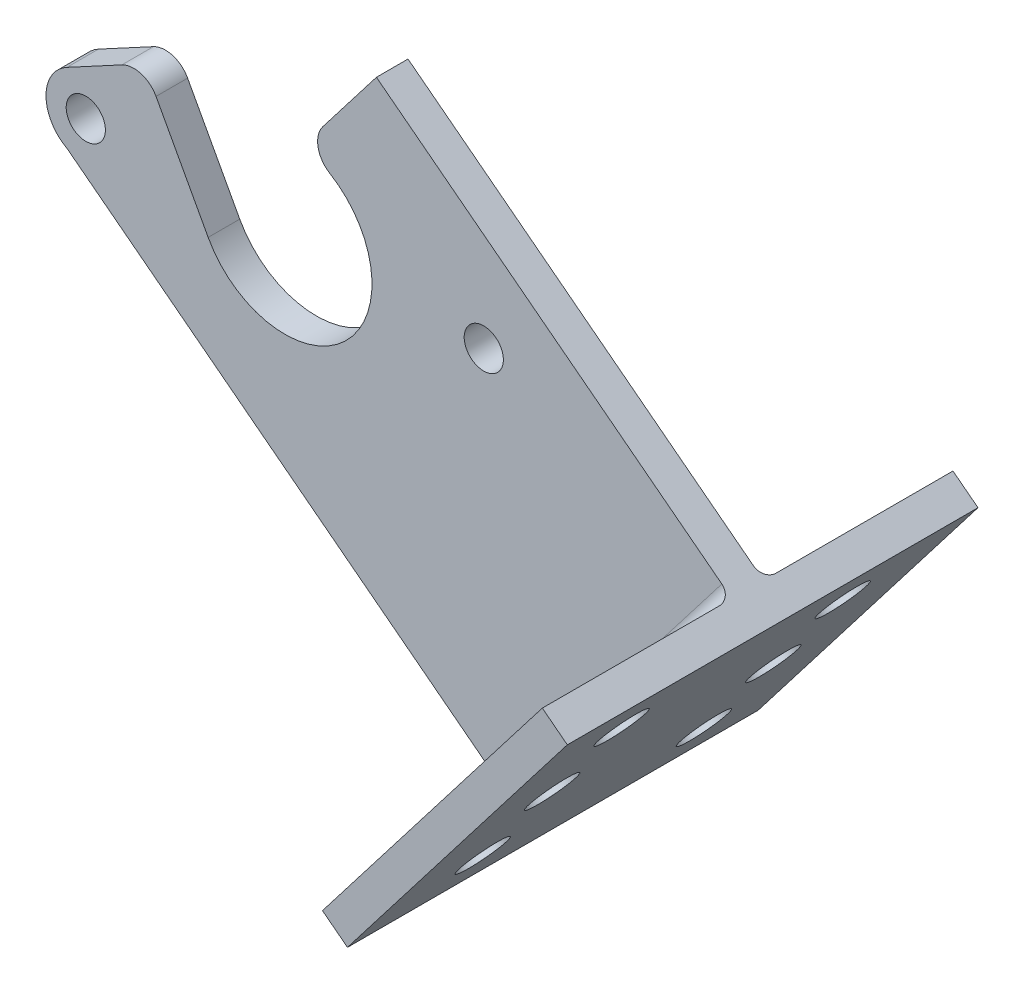
SolidWorks part; units mm, degrees
material "Galvanized Steel"
ref_plane "Front Plane" through (0, 0, 0) normal (0, 0, 1) x (1, 0, 0)
ref_plane "Top Plane" through (0, 0, 0) normal (0, 1, 0) x (1, 0, 0)
ref_plane "Right Plane" through (0, 0, 0) normal (1, 0, 0) x (0, 0, -1)
sketch "Sketch1" plane through (0, 0, 0) normal (0, 0, 1) x (1, 0, 0)
  line L0 (-66.7187, 0.4983) -> (-21.3653, 0.4983) construction
  line L1 (-41.4241, 0.4983) -> (-38.3055, -1.9046)
  line L4 (-29.7212, 15.8934) -> (-45.2196, 7.5407)
  line L6 (38.5759, 0.4983) -> (41.6945, -1.9046)
  line L7 (54.0969, -73.0994) -> (83.8977, -34.4216)
  line L8 (83.8977, -34.4216) -> (54.0969, -73.0994)
  line L9 (-45.2196, -6.544) -> (49.2783, -79.3534)
  line L10 (49.2783, -79.3534) -> (54.0969, -73.0994)
  line L11 (83.8977, -34.4216) -> (93.4704, -21.9974)
  line L12 (93.4704, -21.9974) -> (16.9956, 36.9254)
  line L13 (16.9956, 36.9254) -> (2.149, 17.6562)
  line L14 (-29.7212, 15.8934) -> (-16.8275, -7.8621)
  line L15 (64.2736, 0.4983) -> (66.1757, 0.4983) construction
  line L16 (16.1019, 0.4983) -> (46.5759, 0.4983) construction
  arc A3 (-45.2196, -6.544) -> (-45.2196, 7.5407) centre (-41.4241, 0.4983) cw
  arc A5 (-16.8275, -7.8621) -> (2.149, 17.6562) centre (-1.4241, 0.4983) ccw
  circle A6 centre (38.5759, 0.4983) radius 3.937
  circle A7 centre (-41.4241, 0.4983) radius 3.937
  dimension "D1" = 90
  dimension "D4" = 120.5857
  dimension "D3" = 90
  dimension "D5" = 57.2143
extrude "Boss-Extrude1" add sketch "Sketch1" along normal blind 6.35 contours A5 L14 L4 A3 L9 L10 L7 L11 L12 L13 A7 A6
sketch "Sketch2" plane through (69.2869, -53.3847, 0) normal (0.7921, -0.6103, 0) x (0, 0, -1)
  line L0 (0, 39.6233) -> (38.1, 39.6233)
  line L1 (38.1, 39.6233) -> (38.1, -32.7829)
  line L2 (38.1, -32.7829) -> (0, -32.7829)
  line L3 (-6.35, 39.6233) -> (-44.45, 39.6233)
  line L4 (-44.45, 39.6233) -> (-44.45, -32.7829)
  line L5 (-44.45, -32.7829) -> (-6.35, -32.7829)
  line L6 (-25.4, -32.7829) -> (-25.4, 39.6233) construction
  line L7 (-3.175, -32.7829) -> (-3.175, 39.6233) construction
  line L8 (-6.35, -32.7829) -> (0, -32.7829) construction
  line L9 (-6.35, 39.6233) -> (0, 39.6233) construction
  circle A0 centre (-25.4, 3.4202) radius 4.7625
  circle A2 centre (-25.4, 26.2802) radius 4.7625
  circle A3 centre (-25.4, -19.4398) radius 4.7625
  circle A4 centre (19.05, -19.4398) radius 4.7625
  circle A5 centre (19.05, 26.2802) radius 4.7625
  circle A6 centre (19.05, 3.4202) radius 4.7625
  line M7 (0, -32.7829) -> (0, 39.6233)
  line M9 (-6.35, 39.6233) -> (-6.35, -32.7829)
  dimension "D1" = 2
  dimension "D2" = 2
extrude "Boss-Extrude2" add sketch "Sketch2" against normal blind 6.35 contours L2 L1 L0 A5 A4 A6 M7 | L4 L5 L3 A3 A2 A0 M9
fillet "Fillet1" radius 2.54 2 edges at (66.3442, -46.7998, 6.35) (66.3442, -46.7998, 0)
fillet "Fillet2" radius 5.08 2 edges at (-29.7212, 15.8934, 3.175) (2.149, 17.6562, 3.175)
